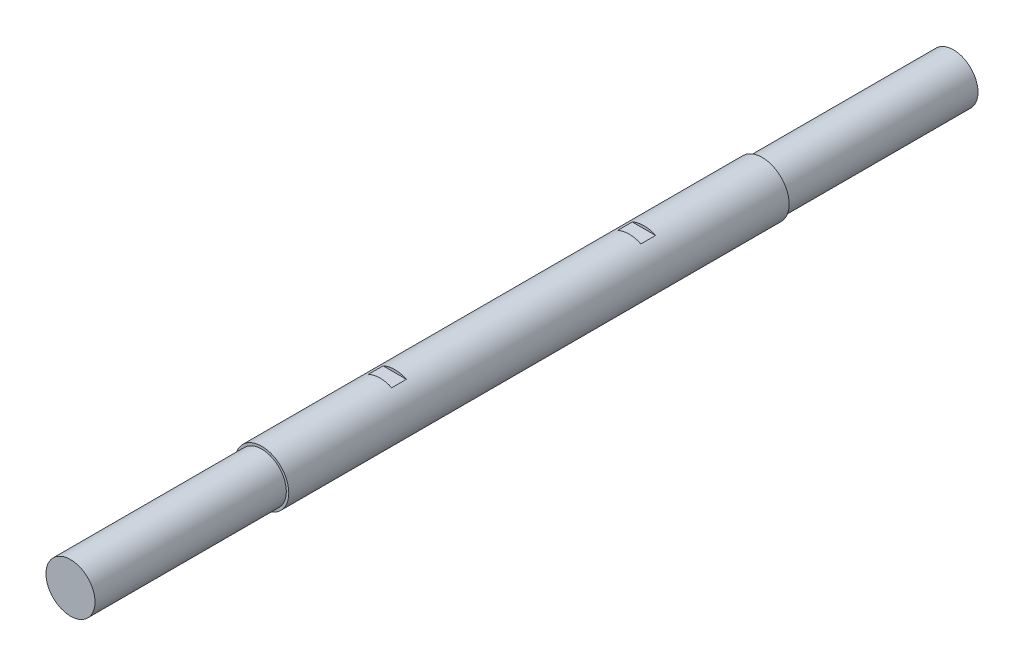
SolidWorks part; units mm, degrees
material "Cast Alloy Steel"
ref_plane "Ön Düzlem" through (0, 0, 0) normal (0, 0, 1) x (1, 0, 0)
ref_plane "Üst Düzlem" through (0, 0, 0) normal (0, 1, 0) x (1, 0, 0)
ref_plane "Sağ Düzlem" through (0, 0, 0) normal (1, 0, 0) x (0, 0, -1)
sketch "Sketch1" plane through (0, 0, 0) normal (1, 0, 0) x (0, 0, -1)
  line L4 (180, 11) -> (-180, 11)
  line L20 (180, 0) -> (-180, 0)
  line L23 (-180, 0) -> (-180, 11)
  line L27 (180, 0) -> (180, 11)
  point P10 (0, 11)
  dimension "D1" = 11
  dimension "D2" = 360
revolve "Revolve1" add sketch "Sketch1" angle 360 about L20
sketch "Sketch4" plane through (0, 0, 0) normal (1, 0, 0) x (0, 0, -1)
  line L0 (180, 11) -> (-180, 11) construction
  line L1 (-53.8, 19.92) -> (-47.8, 19.92)
  line L2 (-53.8, 19.92) -> (-53.8, 9.92)
  line L3 (-53.8, 9.92) -> (-47.8, 9.92)
  line L4 (-47.8, 19.92) -> (-47.8, 9.92)
  point P4 (-50.8, 9.92)
  dimension "D1" = 6
  dimension "D2" = 50.8
  dimension "D3" = 1.08
  dimension "D4" = 10
extrude "Cut-Extrude1" cut sketch "Sketch4" against normal through all and the other way through all
sketch "Sketch6" plane through (0, 0, 0) normal (1, 0, 0) x (0, 0, -1)
  line L1 (-180, 11) -> (-102, 11)
  line L2 (-180, 11) -> (-180, 10)
  line L3 (-180, 10) -> (-102, 10)
  line L4 (-102, 11) -> (-102, 10)
  dimension "D1" = 78
  dimension "D2" = 1
revolve "Cut-Revolve1" cut sketch "Sketch6" angle 360 about axis through (0, 0, -180) along (0, 0, -1)
mirror "Mirror2" about plane through (0, 0, 0) normal (0, 0, 1) of "Cut-Extrude1", "Cut-Revolve1"
